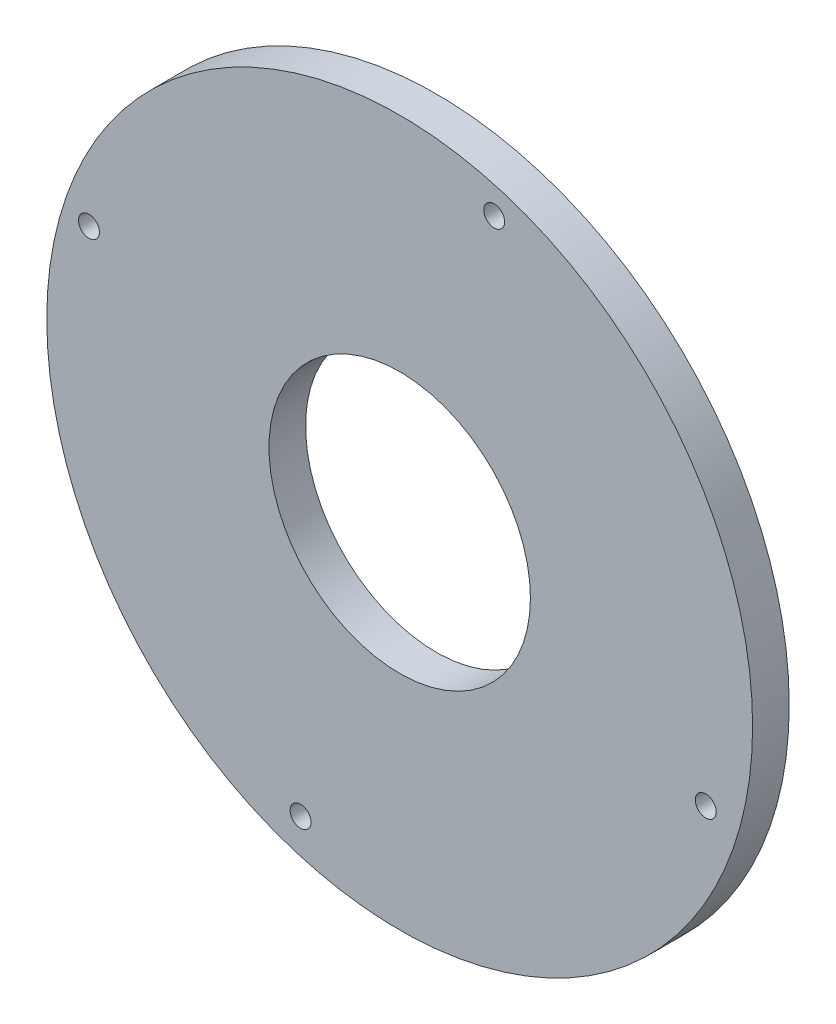
SolidWorks part; units mm, degrees
ref_plane "Piano frontale" through (0, 0, 0) normal (0, 0, 1) x (1, 0, 0)
ref_plane "Piano superiore" through (0, 0, 0) normal (0, 1, 0) x (1, 0, 0)
ref_plane "Piano destro" through (0, 0, 0) normal (1, 0, 0) x (0, 0, -1)
sketch "Schizzo1" plane through (0, 0, 0) normal (0, 0, 1) x (1, 0, 0)
  circle A0 centre (0, 0) radius 135
  dimension "D1" = 270
extrude "Estrusione1" add sketch "Schizzo1" along normal mid plane 14
sketch "Schizzo2" plane through (0, 0, 7) normal (0, 0, 1) x (1, 0, 0)
  circle A0 centre (0, 0) radius 50
  circle A1 centre (-118.8477, 38.7326) radius 4
  circle A2 centre (36.1454, 119.66) radius 4
  circle A3 centre (117.0728, -35.3331) radius 4
  circle A4 centre (-37.9203, -116.2605) radius 4
  dimension "D1" = 100
  dimension "D2" = 8
extrude "Estrusione2" cut sketch "Schizzo2" against normal through all
